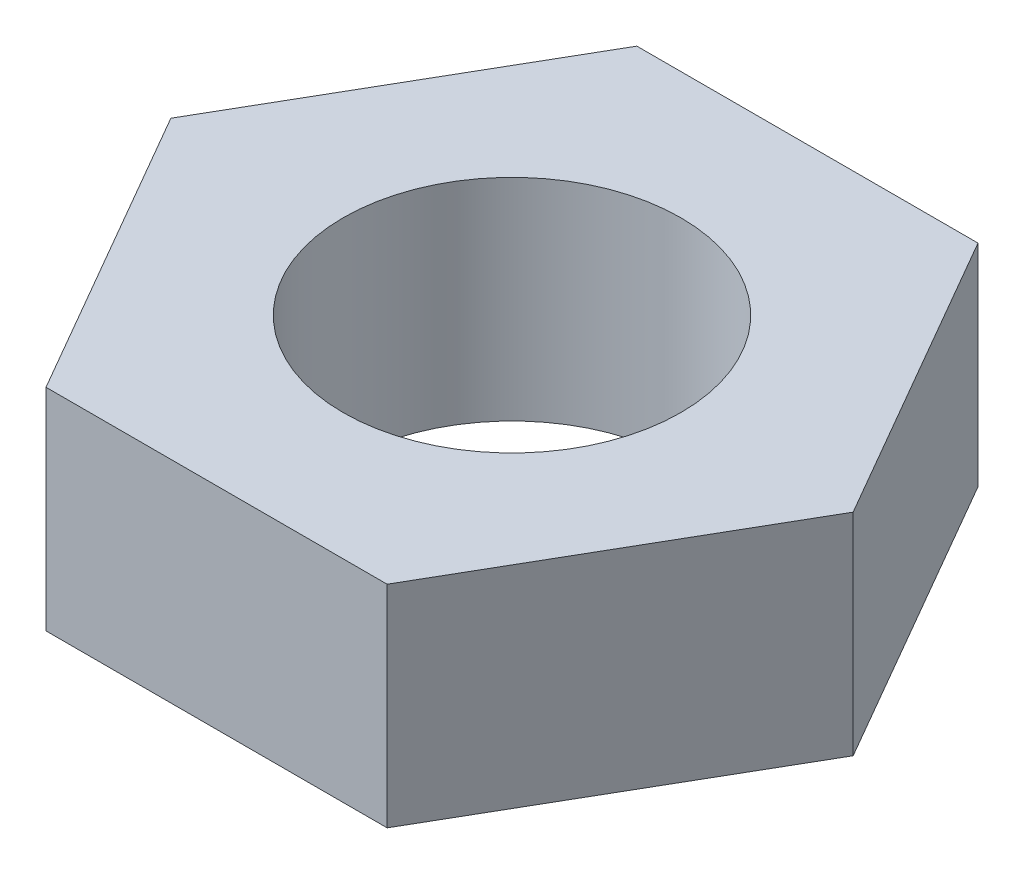
SolidWorks part; units mm, degrees
material "Acier allié"
ref_plane "Face" through (0, 0, 0) normal (0, 0, 1) x (1, 0, 0)
ref_plane "Dessus" through (0, 0, 0) normal (0, 1, 0) x (1, 0, 0)
ref_plane "Droite" through (0, 0, 0) normal (1, 0, 0) x (0, 0, -1)
sketch "Esquisse1" plane through (0, 0, 0) normal (0, 1, 0) x (1, 0, 0)
  line L1 (3.2079, 5.5563) -> (-3.2079, 5.5562)
  line L2 (-3.2079, 5.5562) -> (-6.4158, 0)
  line L3 (-6.4158, 0) -> (-3.2079, -5.5562)
  line L4 (-3.2079, -5.5562) -> (3.2079, -5.5562)
  line L5 (3.2079, -5.5562) -> (6.4158, 0)
  line L6 (6.4158, 0) -> (3.2079, 5.5563)
  circle A0 centre (0, 0) radius 5.5562 construction
  dimension "D1" = 11.1125
extrude "Boss.-Extru.1" add sketch "Esquisse1" along normal blind 3.9688
sketch "Esquisse2" plane through (0, 3.9688, 0) normal (0, 1, 0) x (1, 0, 0)
  circle A0 centre (0, 0) radius 3.175
  dimension "D1" = 6.35
extrude "Enlèv. mat.-Extru.1" cut sketch "Esquisse2" against normal through all
cosmetic thread "Représentation de filetage1" parameters "D2"=6.3754
equation "\"W\"=7 / 16"
equation "\"D1@Esquisse1\"=\"W\""
equation "\"H\"=5/32"
equation "\"D1@Boss.-Extru.1\"=\"H\""
equation "\"D\"=1/4"
equation "\"D1@Esquisse2\"=\"D\""
equation "\"D2@Représentation de filetage1\"=\"D\"+0.001"
